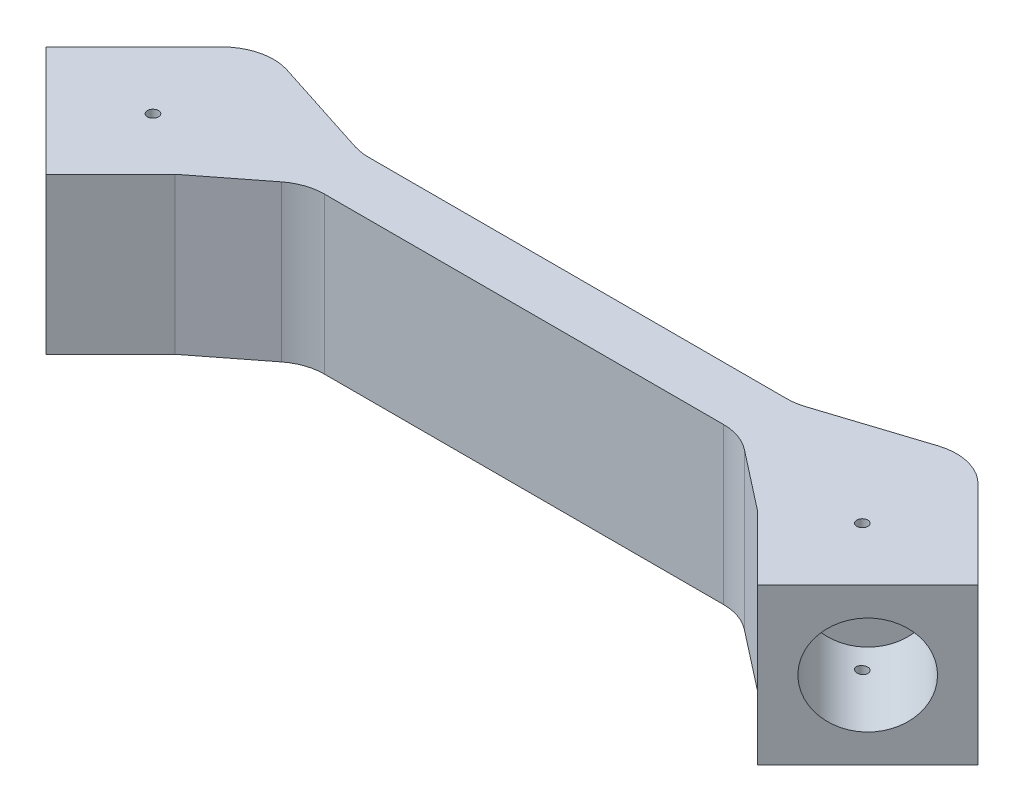
SolidWorks part; units mm, degrees
ref_plane "Front Plane" through (0, 0, 0) normal (0, 0, 1) x (1, 0, 0)
ref_plane "Top Plane" through (0, 0, 0) normal (0, 1, 0) x (1, 0, 0)
ref_plane "Right Plane" through (0, 0, 0) normal (1, 0, 0) x (0, 0, -1)
sketch "Sketch1" plane through (0, 0, 0) normal (0, 1, 0) x (1, 0, 0)
  line L0 (-8.395, 35.7208) -> (16.1076, 27.8284)
  line L5 (0, 0) -> (-15.7815, -15.7815)
  line L6 (-42.7223, 11.1592) -> (-15.7815, -15.7815)
  line L7 (71.12, 38.1) -> (71.12, 0) construction
  line L11 (-21.2689, 32.6126) -> (-42.7223, 11.1592)
  line L12 (20.0013, 27.2168) -> (122.2387, 27.2168)
  line L18 (14.5632, 11.3563) -> (0, 0)
  line L19 (22.3728, 14.0414) -> (119.8672, 14.0414)
  line L20 (142.24, 0) -> (158.0215, -15.7815)
  line L21 (127.6768, 11.3563) -> (142.24, 0)
  line L22 (150.635, 35.7208) -> (126.1324, 27.8284)
  line L23 (163.5089, 32.6126) -> (184.9623, 11.1592)
  line L24 (184.9623, 11.1592) -> (158.0215, -15.7815)
  arc A0 (22.3728, 14.0414) -> (14.5632, 11.3563) centre (22.3728, 1.3414) ccw
  arc A1 (16.1076, 27.8284) -> (20.0013, 27.2168) centre (20.0013, 39.9168) ccw
  arc A2 (-21.2689, 32.6126) -> (-8.395, 35.7208) centre (-12.2886, 23.6324) cw
  arc A3 (126.1324, 27.8284) -> (122.2387, 27.2168) centre (122.2387, 39.9168) cw
  arc A4 (119.8672, 14.0414) -> (127.6768, 11.3563) centre (119.8672, 1.3414) cw
  arc A5 (163.5089, 32.6126) -> (150.635, 35.7208) centre (154.5286, 23.6324) ccw
  point P14 (71.12, 27.2168)
  point P21 (-15.7815, 38.1)
  point P22 (71.12, 14.0414)
  dimension "D2" = 12.7
  dimension "D3" = 38.1
  dimension "D4" = 90
  dimension "D5" = 38.1
  dimension "D6" = 90
  dimension "D7" = 38.1
extrude "Boss-Extrude1" add sketch "Sketch1" along normal blind 38.1
sketch "Sketch2" plane through (-15.7815, 0, 15.7815) normal (-0.7071, 0, 0.7071) x (0.7071, 0, 0.7071)
  line L0 (-38.1, 38.1) -> (0, 0) construction
  line L1 (-38.1, 0) -> (0, 38.1) construction
  circle A0 centre (-19.05, 19.05) radius 12.065
  dimension "D1" = 24.13
extrude "Cut-Extrude1" cut sketch "Sketch2" against normal blind 25.4
sketch "Sketch7" plane through (86.9015, 0, 86.9015) normal (0.7071, 0, 0.7071) x (0.7071, 0, -0.7071)
  line L0 (119.6289, 38.1) -> (119.6289, 0) construction
  line L1 (100.5789, 38.1) -> (138.6789, 38.1) construction
  line L2 (100.5789, 0) -> (138.6789, 0) construction
  line L3 (119.6289, 0) -> (100.5789, 19.05) construction
  line L4 (100.5789, 38.1) -> (100.5789, 0) construction
  line L5 (100.5789, 19.05) -> (138.6789, 19.05) construction
  line L6 (138.6789, 38.1) -> (138.6789, 0) construction
  circle A0 centre (119.6289, 19.05) radius 12.065
  dimension "D1" = 24.13
extrude "Cut-Extrude2" cut sketch "Sketch7" against normal blind 25.4
sketch "Sketch9" plane through (0, 0, -27.2168) normal (0, 0, -1) x (-1, 0, 0)
  line L0 (-71.12, 38.1) -> (-71.12, 0) construction
  line L1 (-122.2387, 38.1) -> (-20.0013, 38.1) construction
  line L2 (-122.2387, 0) -> (-20.0013, 0) construction
  line L3 (-122.2387, 19.05) -> (-20.0013, 19.05) construction
  line L4 (-122.2387, 38.1) -> (-122.2387, 0) construction
  line L5 (-20.0013, 38.1) -> (-20.0013, 0) construction
  line L6 (-84.2645, 26.289) -> (-84.2645, 0)
  line L7 (-84.2645, 26.289) -> (-57.9755, 26.289)
  line L8 (-57.9755, 26.289) -> (-57.9755, 0)
  line L13 (-122.2387, 0) -> (-20.0013, 0)
  line L14 (-20.0013, 0) -> (-20.0013, 38.1)
  line L15 (-20.0013, 38.1) -> (-122.2387, 38.1)
  line L16 (-122.2387, 38.1) -> (-122.2387, 0)
  line L17 (-84.2645, 0) -> (-57.9755, 0)
  point P14 (-71.12, 26.289)
  dimension "D1" = 26.289
  dimension "D2" = 26.289
  dimension "D3" = 0
extrude "Boss-Extrude3" add sketch "Sketch9" along normal blind 8.89
sketch "Sketch10" plane through (0, 0, -36.1068) normal (0, 0, -1) x (-1, 0, 0)
  line L0 (-71.12, 26.289) -> (-71.12, 0) construction
  line L1 (-57.9755, 26.289) -> (-84.2645, 26.289) construction
  line L2 (-84.2645, 0) -> (-57.9755, 0) construction
  line L3 (-84.2645, 13.1445) -> (-57.9755, 13.1445) construction
  line L4 (-84.2645, 26.289) -> (-84.2645, 0) construction
  line L5 (-57.9755, 0) -> (-57.9755, 26.289) construction
  circle A0 centre (-71.12, 13.1445) radius 8.0645
  dimension "D1" = 16.129
extrude "Cut-Extrude3" cut sketch "Sketch10" against normal blind 6.35
sketch "Sketch12" plane through (0, 0, -29.7568) normal (0, 0, -1) x (-1, 0, 0)
  line L0 (-71.12, 21.209) -> (-71.12, 5.08) construction
  circle A0 centre (-71.12, 13.1445) radius 8.0645 construction
  circle A1 centre (-71.12, 13.1445) radius 8.0645 construction
  circle A2 centre (-71.12, 13.1445) radius 6.35
  dimension "D1" = 12.7
extrude "Cut-Extrude5" cut sketch "Sketch12" against normal blind 5.08
fillet "Fillet1" radius 12.7 2 edges at (57.9755, 26.289, -31.6618) (84.2645, 26.289, -31.6618)
sketch "Sketch13" plane through (0, 38.1, 0) normal (0, 1, 0) x (1, 0, 0)
  line L0 (-15.2692, 35.9777) -> (-15.7815, -15.7815) construction
  line L1 (71.12, 27.2168) -> (71.12, 14.0414) construction
  line L2 (122.2387, 27.2168) -> (20.0013, 27.2168) construction
  line L3 (22.3728, 14.0414) -> (119.8672, 14.0414) construction
  arc A0 (-8.395, 35.7208) -> (-21.2689, 32.6126) centre (-12.2886, 23.6324) ccw construction
  circle A2 centre (-15.5253, 10.0981) radius 1.35
  circle A3 centre (157.7653, 10.0981) radius 1.35
  dimension "D1" = 2.7
extrude "Cut-Extrude6" cut sketch "Sketch13" against normal blind 51.816
